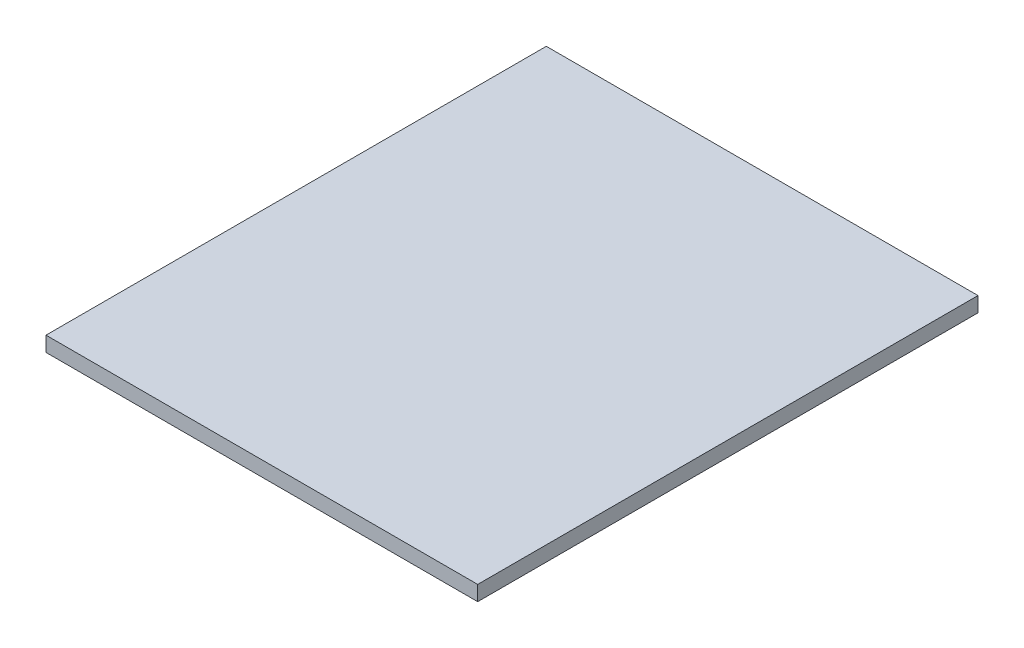
SolidWorks part; units mm, degrees
ref_plane "Front Plane" through (0, 0, 0) normal (0, 0, 1) x (1, 0, 0)
ref_plane "Top Plane" through (0, 0, 0) normal (0, 1, 0) x (1, 0, 0)
ref_plane "Right Plane" through (0, 0, 0) normal (1, 0, 0) x (0, 0, -1)
sketch "Sketch2" plane through (0, 0, 0) normal (0, 1, 0) x (1, 0, 0)
  line L0 (0, 0) -> (40.6756, 0)
  line L1 (40.6756, 0) -> (40.6756, 47.1399)
  line L2 (40.6756, 47.1399) -> (0, 47.1399)
  line L3 (0, 47.1399) -> (0, 0)
extrude "Boss-Extrude1" add sketch "Sketch2" along normal blind 1.4122
